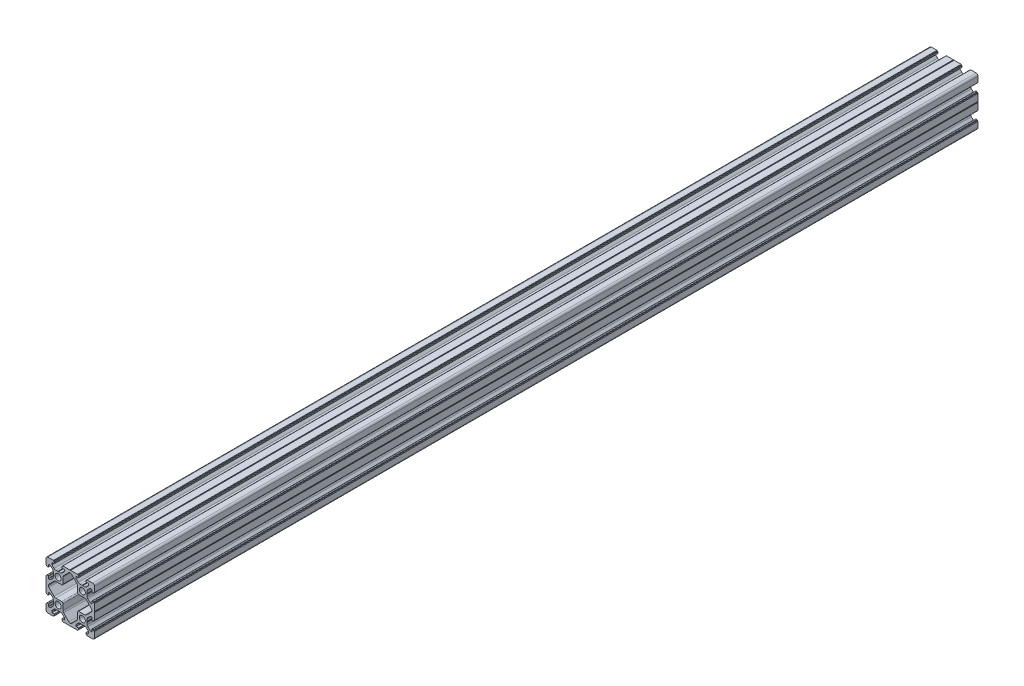
SolidWorks part; units mm, degrees
ref_plane "Спереди" through (0, 0, 0) normal (0, 0, 1) x (1, 0, 0)
ref_plane "Сверху" through (0, 0, 0) normal (0, 1, 0) x (1, 0, 0)
ref_plane "Справа" through (0, 0, 0) normal (1, 0, 0) x (0, 0, -1)
sketch "Эскиз3" plane through (0, 0, 0) normal (0, 0, 1) x (1, 0, 0)
  line L0 (-18.5, -18.5) -> (18.5, 18.5) construction
  line L1 (28.0099, -28.0099) -> (-35327.3285, 35327.3285) construction
  line L2 (-7, 6) -> (-11.9302, 6)
  line L3 (-13.3492, 5.4094) -> (-17.5933, 1.1367)
  line L4 (-18, 0.1501) -> (-18, -0.1501)
  line L5 (-13.3492, -5.4094) -> (-17.5933, -1.1367)
  line L6 (-7, -6) -> (-11.9302, -6)
  line L7 (6, -7) -> (6, -11.9302)
  line L8 (-6, -7) -> (-6, -11.9302)
  line L9 (-5.4094, -13.3492) -> (-1.1367, -17.5933)
  line L10 (-0.1501, -18) -> (0.1501, -18)
  line L11 (5.4094, -13.3492) -> (1.1367, -17.5933)
  line L12 (6, 7) -> (6, 11.9302)
  line L13 (5.4094, 13.3492) -> (1.1367, 17.5933)
  line L14 (0.1501, 18) -> (-0.1501, 18)
  line L15 (-5.4094, 13.3492) -> (-1.1367, 17.5933)
  line L16 (-6, 7) -> (-6, 11.9302)
  line L17 (7, -6) -> (11.9302, -6)
  line L18 (13.3492, -5.4094) -> (17.5933, -1.1367)
  line L19 (18, -0.1501) -> (18, 0.1501)
  line L20 (13.3492, 5.4094) -> (17.5933, 1.1367)
  line L21 (7, 6) -> (11.9302, 6)
  line L544 (0.237, 19.958) -> (0, 19.8)
  line L545 (0, 19.8) -> (-0.237, 19.958)
  line L546 (-0.3757, 20) -> (-6.05, 20)
  line L547 (-6.3, 19.75) -> (-6.3, 19.4)
  line L548 (-6.3, 19.4) -> (-6.68, 19.4)
  line L549 (-6.93, 19.15) -> (-6.93, 18.25)
  line L550 (-6.68, 18) -> (-5, 18)
  line L551 (-4.8, 17.8) -> (-4.8, 16.8517)
  line L552 (-5.0929, 16.1445) -> (-6.6517, 14.5858)
  line L553 (-8.0659, 14) -> (-9.6623, 14)
  line L554 (-9.8185, 13.9452) -> (-10, 13.8)
  line L555 (-10, 13.8) -> (-10.1815, 13.9452)
  line L556 (-10.3377, 14) -> (-11.9341, 14)
  line L557 (-13.3483, 14.5858) -> (-14.9071, 16.1445)
  line L558 (-15.2, 16.8517) -> (-15.2, 17.8)
  line L559 (-15, 18) -> (-13.32, 18)
  line L560 (-13.07, 18.25) -> (-13.07, 19.15)
  line L561 (-13.32, 19.4) -> (-13.7, 19.4)
  line L562 (-13.7, 19.4) -> (-13.7, 19.75)
  line L563 (-13.95, 20) -> (-18.5, 20)
  line L564 (-20, 18.5) -> (-20, 13.95)
  line L565 (-19.75, 13.7) -> (-19.4, 13.7)
  line L566 (-19.4, 13.7) -> (-19.4, 13.32)
  line L567 (-19.15, 13.07) -> (-18.25, 13.07)
  line L568 (-18, 13.32) -> (-18, 15)
  line L569 (-17.8, 15.2) -> (-16.8517, 15.2)
  line L570 (-16.1445, 14.9071) -> (-14.5858, 13.3483)
  line L571 (-14, 11.9341) -> (-14, 10.3377)
  line L572 (-13.9452, 10.1815) -> (-13.8, 10)
  line L573 (-13.8, 10) -> (-13.9452, 9.8185)
  line L574 (-14, 9.6623) -> (-14, 8.0659)
  line L575 (-14.5858, 6.6517) -> (-16.1445, 5.0929)
  line L576 (-16.8517, 4.8) -> (-17.8, 4.8)
  line L577 (-18, 5) -> (-18, 6.68)
  line L578 (-18.25, 6.93) -> (-19.15, 6.93)
  line L579 (-19.4, 6.68) -> (-19.4, 6.3)
  line L580 (-19.4, 6.3) -> (-19.75, 6.3)
  line L581 (-20, 6.05) -> (-20, 0.3757)
  line L582 (-19.958, 0.237) -> (-19.8, 0)
  line L583 (-19.8, 0) -> (-19.958, -0.237)
  line L584 (-20, -0.3757) -> (-20, -6.05)
  line L585 (-19.75, -6.3) -> (-19.4, -6.3)
  line L586 (-19.4, -6.3) -> (-19.4, -6.68)
  line L587 (-19.15, -6.93) -> (-18.25, -6.93)
  line L588 (-18, -6.68) -> (-18, -5)
  line L589 (-17.8, -4.8) -> (-16.8517, -4.8)
  line L590 (-16.1445, -5.0929) -> (-14.5858, -6.6517)
  line L591 (-14, -8.0659) -> (-14, -9.6623)
  line L592 (-13.9452, -9.8185) -> (-13.8, -10)
  line L593 (-13.8, -10) -> (-13.9452, -10.1815)
  line L594 (-14, -10.3377) -> (-14, -11.9341)
  line L595 (-14.5858, -13.3483) -> (-16.1445, -14.9071)
  line L596 (-16.8517, -15.2) -> (-17.8, -15.2)
  line L597 (-18, -15) -> (-18, -13.32)
  line L598 (-18.25, -13.07) -> (-19.15, -13.07)
  line L599 (-19.4, -13.32) -> (-19.4, -13.7)
  line L600 (-19.4, -13.7) -> (-19.75, -13.7)
  line L601 (-20, -13.95) -> (-20, -18.5)
  line L602 (-18.5, -20) -> (-13.95, -20)
  line L603 (-13.7, -19.75) -> (-13.7, -19.4)
  line L604 (-13.7, -19.4) -> (-13.32, -19.4)
  line L605 (-13.07, -19.15) -> (-13.07, -18.25)
  line L606 (-13.32, -18) -> (-15, -18)
  line L607 (-15.2, -17.8) -> (-15.2, -16.8517)
  line L608 (-14.9071, -16.1445) -> (-13.3483, -14.5858)
  line L609 (-11.9341, -14) -> (-10.3377, -14)
  line L610 (-10.1815, -13.9452) -> (-10, -13.8)
  line L611 (-10, -13.8) -> (-9.8185, -13.9452)
  line L612 (-9.6623, -14) -> (-8.0659, -14)
  line L613 (-6.6517, -14.5858) -> (-5.0929, -16.1445)
  line L614 (-4.8, -16.8517) -> (-4.8, -17.8)
  line L615 (-5, -18) -> (-6.68, -18)
  line L616 (-6.93, -18.25) -> (-6.93, -19.15)
  line L617 (-6.68, -19.4) -> (-6.3, -19.4)
  line L618 (-6.3, -19.4) -> (-6.3, -19.75)
  line L619 (-6.05, -20) -> (-0.3757, -20)
  line L620 (-0.237, -19.958) -> (0, -19.8)
  line L621 (0, -19.8) -> (0.237, -19.958)
  line L622 (0.3757, -20) -> (6.05, -20)
  line L623 (6.3, -19.75) -> (6.3, -19.4)
  line L624 (6.3, -19.4) -> (6.68, -19.4)
  line L625 (6.93, -19.15) -> (6.93, -18.25)
  line L626 (6.68, -18) -> (5, -18)
  line L627 (4.8, -17.8) -> (4.8, -16.8517)
  line L628 (5.0929, -16.1445) -> (6.6517, -14.5858)
  line L629 (8.0659, -14) -> (9.6623, -14)
  line L630 (9.8185, -13.9452) -> (10, -13.8)
  line L631 (10, -13.8) -> (10.1815, -13.9452)
  line L632 (10.3377, -14) -> (11.9341, -14)
  line L633 (13.3483, -14.5858) -> (14.9071, -16.1445)
  line L634 (15.2, -16.8517) -> (15.2, -17.8)
  line L635 (15, -18) -> (13.32, -18)
  line L636 (13.07, -18.25) -> (13.07, -19.15)
  line L637 (13.32, -19.4) -> (13.7, -19.4)
  line L638 (13.7, -19.4) -> (13.7, -19.75)
  line L639 (13.95, -20) -> (18.5, -20)
  line L640 (20, -18.5) -> (20, -13.95)
  line L641 (19.75, -13.7) -> (19.4, -13.7)
  line L642 (19.4, -13.7) -> (19.4, -13.32)
  line L643 (19.15, -13.07) -> (18.25, -13.07)
  line L644 (18, -13.32) -> (18, -15)
  line L645 (17.8, -15.2) -> (16.8517, -15.2)
  line L646 (16.1445, -14.9071) -> (14.5858, -13.3483)
  line L647 (14, -11.9341) -> (14, -10.3377)
  line L648 (13.9452, -10.1815) -> (13.8, -10)
  line L649 (13.8, -10) -> (13.9452, -9.8185)
  line L650 (14, -9.6623) -> (14, -8.0659)
  line L651 (14.5858, -6.6517) -> (16.1445, -5.0929)
  line L652 (16.8517, -4.8) -> (17.8, -4.8)
  line L653 (18, -5) -> (18, -6.68)
  line L654 (18.25, -6.93) -> (19.15, -6.93)
  line L655 (19.4, -6.68) -> (19.4, -6.3)
  line L656 (19.4, -6.3) -> (19.75, -6.3)
  line L657 (20, -6.05) -> (20, -0.3757)
  line L658 (19.958, -0.237) -> (19.8, 0)
  line L659 (19.8, 0) -> (19.958, 0.237)
  line L660 (20, 0.3757) -> (20, 6.05)
  line L661 (19.75, 6.3) -> (19.4, 6.3)
  line L662 (19.4, 6.3) -> (19.4, 6.68)
  line L663 (19.15, 6.93) -> (18.25, 6.93)
  line L664 (18, 6.68) -> (18, 5)
  line L665 (17.8, 4.8) -> (16.8517, 4.8)
  line L666 (16.1445, 5.0929) -> (14.5858, 6.6517)
  line L667 (14, 8.0659) -> (14, 9.6623)
  line L668 (13.9452, 9.8185) -> (13.8, 10)
  line L669 (13.8, 10) -> (13.9452, 10.1815)
  line L670 (14, 10.3377) -> (14, 11.9341)
  line L671 (14.5858, 13.3483) -> (16.1445, 14.9071)
  line L672 (16.8517, 15.2) -> (17.8, 15.2)
  line L673 (18, 15) -> (18, 13.32)
  line L674 (18.25, 13.07) -> (19.15, 13.07)
  line L675 (19.4, 13.32) -> (19.4, 13.7)
  line L676 (19.4, 13.7) -> (19.75, 13.7)
  line L677 (20, 13.95) -> (20, 18.5)
  line L678 (18.5, 20) -> (13.95, 20)
  line L679 (13.7, 19.75) -> (13.7, 19.4)
  line L680 (13.7, 19.4) -> (13.32, 19.4)
  line L681 (13.07, 19.15) -> (13.07, 18.25)
  line L682 (13.32, 18) -> (15, 18)
  line L683 (15.2, 17.8) -> (15.2, 16.8517)
  line L684 (14.9071, 16.1445) -> (13.3483, 14.5858)
  line L685 (11.9341, 14) -> (10.3377, 14)
  line L686 (10.1815, 13.9452) -> (10, 13.8)
  line L687 (10, 13.8) -> (9.8185, 13.9452)
  line L688 (9.6623, 14) -> (8.0659, 14)
  line L689 (6.6517, 14.5858) -> (5.0929, 16.1445)
  line L690 (4.8, 16.8517) -> (4.8, 17.8)
  line L691 (5, 18) -> (6.68, 18)
  line L692 (6.93, 18.25) -> (6.93, 19.15)
  line L693 (6.68, 19.4) -> (6.3, 19.4)
  line L694 (6.3, 19.4) -> (6.3, 19.75)
  line L695 (6.05, 20) -> (0.3757, 20)
  arc A0 (-7, 6) -> (-6, 7) centre (-7, 7) ccw
  arc A1 (-11.9302, 6) -> (-13.3492, 5.4094) centre (-11.9302, 4) ccw
  arc A2 (-17.5933, 1.1367) -> (-18, 0.1501) centre (-16.6, 0.1501) ccw
  arc A3 (-18, -0.1501) -> (-17.5933, -1.1367) centre (-16.6, -0.1501) ccw
  arc A4 (-13.3492, -5.4094) -> (-11.9302, -6) centre (-11.9302, -4) ccw
  arc A5 (6, 7) -> (7, 6) centre (7, 7) ccw
  arc A6 (6, 11.9302) -> (5.4094, 13.3492) centre (4, 11.9302) ccw
  arc A7 (1.1367, 17.5933) -> (0.1501, 18) centre (0.1501, 16.6) ccw
  arc A8 (7.5, 10) -> (12.5, 10) centre (10, 10) ccw
  arc A9 (12.5, 10) -> (7.5, 10) centre (10, 10) ccw
  arc A10 (-7.5, 10) -> (-12.5, 10) centre (-10, 10) ccw
  arc A11 (-12.5, 10) -> (-7.5, 10) centre (-10, 10) ccw
  arc A12 (-7.5, -10) -> (-12.5, -10) centre (-10, -10) ccw
  arc A13 (-12.5, -10) -> (-7.5, -10) centre (-10, -10) ccw
  arc A14 (12.5, -10) -> (7.5, -10) centre (10, -10) ccw
  arc A15 (7.5, -10) -> (12.5, -10) centre (10, -10) ccw
  arc A16 (-0.1501, 18) -> (-1.1367, 17.5933) centre (-0.1501, 16.6) ccw
  arc A17 (-5.4094, 13.3492) -> (-6, 11.9302) centre (-4, 11.9302) ccw
  arc A18 (7, -6) -> (6, -7) centre (7, -7) ccw
  arc A19 (11.9302, -6) -> (13.3492, -5.4094) centre (11.9302, -4) ccw
  arc A20 (17.5933, -1.1367) -> (18, -0.1501) centre (16.6, -0.1501) ccw
  arc A21 (18, 0.1501) -> (17.5933, 1.1367) centre (16.6, 0.1501) ccw
  arc A22 (13.3492, 5.4094) -> (11.9302, 6) centre (11.9302, 4) ccw
  arc A23 (5.4094, -13.3492) -> (6, -11.9302) centre (4, -11.9302) ccw
  arc A24 (-6, -7) -> (-7, -6) centre (-7, -7) ccw
  arc A25 (-6, -11.9302) -> (-5.4094, -13.3492) centre (-4, -11.9302) ccw
  arc A26 (-1.1367, -17.5933) -> (-0.1501, -18) centre (-0.1501, -16.6) ccw
  arc A27 (0.1501, -18) -> (1.1367, -17.5933) centre (0.1501, -16.6) ccw
  arc A464 (-0.237, 19.958) -> (-0.3757, 20) centre (-0.3757, 19.75) ccw
  arc A465 (-6.05, 20) -> (-6.3, 19.75) centre (-6.05, 19.75) ccw
  arc A466 (-6.68, 19.4) -> (-6.93, 19.15) centre (-6.68, 19.15) ccw
  arc A467 (-6.93, 18.25) -> (-6.68, 18) centre (-6.68, 18.25) ccw
  arc A468 (-4.8, 17.8) -> (-5, 18) centre (-5, 17.8) ccw
  arc A469 (-5.0929, 16.1445) -> (-4.8, 16.8517) centre (-5.8, 16.8517) ccw
  arc A470 (-8.0659, 14) -> (-6.6517, 14.5858) centre (-8.0659, 16) ccw
  arc A471 (-9.6623, 14) -> (-9.8185, 13.9452) centre (-9.6623, 13.75) ccw
  arc A472 (-10.1815, 13.9452) -> (-10.3377, 14) centre (-10.3377, 13.75) ccw
  arc A473 (-13.3483, 14.5858) -> (-11.9341, 14) centre (-11.9341, 16) ccw
  arc A474 (-15.2, 16.8517) -> (-14.9071, 16.1445) centre (-14.2, 16.8517) ccw
  arc A475 (-15, 18) -> (-15.2, 17.8) centre (-15, 17.8) ccw
  arc A476 (-13.32, 18) -> (-13.07, 18.25) centre (-13.32, 18.25) ccw
  arc A477 (-13.07, 19.15) -> (-13.32, 19.4) centre (-13.32, 19.15) ccw
  arc A478 (-13.7, 19.75) -> (-13.95, 20) centre (-13.95, 19.75) ccw
  arc A479 (-18.5, 20) -> (-20, 18.5) centre (-18.5, 18.5) ccw
  arc A480 (-20, 13.95) -> (-19.75, 13.7) centre (-19.75, 13.95) ccw
  arc A481 (-19.4, 13.32) -> (-19.15, 13.07) centre (-19.15, 13.32) ccw
  arc A482 (-18.25, 13.07) -> (-18, 13.32) centre (-18.25, 13.32) ccw
  arc A483 (-17.8, 15.2) -> (-18, 15) centre (-17.8, 15) ccw
  arc A484 (-16.1445, 14.9071) -> (-16.8517, 15.2) centre (-16.8517, 14.2) ccw
  arc A485 (-14, 11.9341) -> (-14.5858, 13.3483) centre (-16, 11.9341) ccw
  arc A486 (-14, 10.3377) -> (-13.9452, 10.1815) centre (-13.75, 10.3377) ccw
  arc A487 (-13.9452, 9.8185) -> (-14, 9.6623) centre (-13.75, 9.6623) ccw
  arc A488 (-14.5858, 6.6517) -> (-14, 8.0659) centre (-16, 8.0659) ccw
  arc A489 (-16.8517, 4.8) -> (-16.1445, 5.0929) centre (-16.8517, 5.8) ccw
  arc A490 (-18, 5) -> (-17.8, 4.8) centre (-17.8, 5) ccw
  arc A491 (-18, 6.68) -> (-18.25, 6.93) centre (-18.25, 6.68) ccw
  arc A492 (-19.15, 6.93) -> (-19.4, 6.68) centre (-19.15, 6.68) ccw
  arc A493 (-19.75, 6.3) -> (-20, 6.05) centre (-19.75, 6.05) ccw
  arc A494 (-20, 0.3757) -> (-19.958, 0.237) centre (-19.75, 0.3757) ccw
  arc A495 (-19.958, -0.237) -> (-20, -0.3757) centre (-19.75, -0.3757) ccw
  arc A496 (-20, -6.05) -> (-19.75, -6.3) centre (-19.75, -6.05) ccw
  arc A497 (-19.4, -6.68) -> (-19.15, -6.93) centre (-19.15, -6.68) ccw
  arc A498 (-18.25, -6.93) -> (-18, -6.68) centre (-18.25, -6.68) ccw
  arc A499 (-17.8, -4.8) -> (-18, -5) centre (-17.8, -5) ccw
  arc A500 (-16.1445, -5.0929) -> (-16.8517, -4.8) centre (-16.8517, -5.8) ccw
  arc A501 (-14, -8.0659) -> (-14.5858, -6.6517) centre (-16, -8.0659) ccw
  arc A502 (-14, -9.6623) -> (-13.9452, -9.8185) centre (-13.75, -9.6623) ccw
  arc A503 (-13.9452, -10.1815) -> (-14, -10.3377) centre (-13.75, -10.3377) ccw
  arc A504 (-14.5858, -13.3483) -> (-14, -11.9341) centre (-16, -11.9341) ccw
  arc A505 (-16.8517, -15.2) -> (-16.1445, -14.9071) centre (-16.8517, -14.2) ccw
  arc A506 (-18, -15) -> (-17.8, -15.2) centre (-17.8, -15) ccw
  arc A507 (-18, -13.32) -> (-18.25, -13.07) centre (-18.25, -13.32) ccw
  arc A508 (-19.15, -13.07) -> (-19.4, -13.32) centre (-19.15, -13.32) ccw
  arc A509 (-19.75, -13.7) -> (-20, -13.95) centre (-19.75, -13.95) ccw
  arc A510 (-20, -18.5) -> (-18.5, -20) centre (-18.5, -18.5) ccw
  arc A511 (-13.95, -20) -> (-13.7, -19.75) centre (-13.95, -19.75) ccw
  arc A512 (-13.32, -19.4) -> (-13.07, -19.15) centre (-13.32, -19.15) ccw
  arc A513 (-13.07, -18.25) -> (-13.32, -18) centre (-13.32, -18.25) ccw
  arc A514 (-15.2, -17.8) -> (-15, -18) centre (-15, -17.8) ccw
  arc A515 (-14.9071, -16.1445) -> (-15.2, -16.8517) centre (-14.2, -16.8517) ccw
  arc A516 (-11.9341, -14) -> (-13.3483, -14.5858) centre (-11.9341, -16) ccw
  arc A517 (-10.3377, -14) -> (-10.1815, -13.9452) centre (-10.3377, -13.75) ccw
  arc A518 (-9.8185, -13.9452) -> (-9.6623, -14) centre (-9.6623, -13.75) ccw
  arc A519 (-6.6517, -14.5858) -> (-8.0659, -14) centre (-8.0659, -16) ccw
  arc A520 (-4.8, -16.8517) -> (-5.0929, -16.1445) centre (-5.8, -16.8517) ccw
  arc A521 (-5, -18) -> (-4.8, -17.8) centre (-5, -17.8) ccw
  arc A522 (-6.68, -18) -> (-6.93, -18.25) centre (-6.68, -18.25) ccw
  arc A523 (-6.93, -19.15) -> (-6.68, -19.4) centre (-6.68, -19.15) ccw
  arc A524 (-6.3, -19.75) -> (-6.05, -20) centre (-6.05, -19.75) ccw
  arc A525 (-0.3757, -20) -> (-0.237, -19.958) centre (-0.3757, -19.75) ccw
  arc A526 (0.237, -19.958) -> (0.3757, -20) centre (0.3757, -19.75) ccw
  arc A527 (6.05, -20) -> (6.3, -19.75) centre (6.05, -19.75) ccw
  arc A528 (6.68, -19.4) -> (6.93, -19.15) centre (6.68, -19.15) ccw
  arc A529 (6.93, -18.25) -> (6.68, -18) centre (6.68, -18.25) ccw
  arc A530 (4.8, -17.8) -> (5, -18) centre (5, -17.8) ccw
  arc A531 (5.0929, -16.1445) -> (4.8, -16.8517) centre (5.8, -16.8517) ccw
  arc A532 (8.0659, -14) -> (6.6517, -14.5858) centre (8.0659, -16) ccw
  arc A533 (9.6623, -14) -> (9.8185, -13.9452) centre (9.6623, -13.75) ccw
  arc A534 (10.1815, -13.9452) -> (10.3377, -14) centre (10.3377, -13.75) ccw
  arc A535 (13.3483, -14.5858) -> (11.9341, -14) centre (11.9341, -16) ccw
  arc A536 (15.2, -16.8517) -> (14.9071, -16.1445) centre (14.2, -16.8517) ccw
  arc A537 (15, -18) -> (15.2, -17.8) centre (15, -17.8) ccw
  arc A538 (13.32, -18) -> (13.07, -18.25) centre (13.32, -18.25) ccw
  arc A539 (13.07, -19.15) -> (13.32, -19.4) centre (13.32, -19.15) ccw
  arc A540 (13.7, -19.75) -> (13.95, -20) centre (13.95, -19.75) ccw
  arc A541 (18.5, -20) -> (20, -18.5) centre (18.5, -18.5) ccw
  arc A542 (20, -13.95) -> (19.75, -13.7) centre (19.75, -13.95) ccw
  arc A543 (19.4, -13.32) -> (19.15, -13.07) centre (19.15, -13.32) ccw
  arc A544 (18.25, -13.07) -> (18, -13.32) centre (18.25, -13.32) ccw
  arc A545 (17.8, -15.2) -> (18, -15) centre (17.8, -15) ccw
  arc A546 (16.1445, -14.9071) -> (16.8517, -15.2) centre (16.8517, -14.2) ccw
  arc A547 (14, -11.9341) -> (14.5858, -13.3483) centre (16, -11.9341) ccw
  arc A548 (14, -10.3377) -> (13.9452, -10.1815) centre (13.75, -10.3377) ccw
  arc A549 (13.9452, -9.8185) -> (14, -9.6623) centre (13.75, -9.6623) ccw
  arc A550 (14.5858, -6.6517) -> (14, -8.0659) centre (16, -8.0659) ccw
  arc A551 (16.8517, -4.8) -> (16.1445, -5.0929) centre (16.8517, -5.8) ccw
  arc A552 (18, -5) -> (17.8, -4.8) centre (17.8, -5) ccw
  arc A553 (18, -6.68) -> (18.25, -6.93) centre (18.25, -6.68) ccw
  arc A554 (19.15, -6.93) -> (19.4, -6.68) centre (19.15, -6.68) ccw
  arc A555 (19.75, -6.3) -> (20, -6.05) centre (19.75, -6.05) ccw
  arc A556 (20, -0.3757) -> (19.958, -0.237) centre (19.75, -0.3757) ccw
  arc A557 (19.958, 0.237) -> (20, 0.3757) centre (19.75, 0.3757) ccw
  arc A558 (20, 6.05) -> (19.75, 6.3) centre (19.75, 6.05) ccw
  arc A559 (19.4, 6.68) -> (19.15, 6.93) centre (19.15, 6.68) ccw
  arc A560 (18.25, 6.93) -> (18, 6.68) centre (18.25, 6.68) ccw
  arc A561 (17.8, 4.8) -> (18, 5) centre (17.8, 5) ccw
  arc A562 (16.1445, 5.0929) -> (16.8517, 4.8) centre (16.8517, 5.8) ccw
  arc A563 (14, 8.0659) -> (14.5858, 6.6517) centre (16, 8.0659) ccw
  arc A564 (14, 9.6623) -> (13.9452, 9.8185) centre (13.75, 9.6623) ccw
  arc A565 (13.9452, 10.1815) -> (14, 10.3377) centre (13.75, 10.3377) ccw
  arc A566 (14.5858, 13.3483) -> (14, 11.9341) centre (16, 11.9341) ccw
  arc A567 (16.8517, 15.2) -> (16.1445, 14.9071) centre (16.8517, 14.2) ccw
  arc A568 (18, 15) -> (17.8, 15.2) centre (17.8, 15) ccw
  arc A569 (18, 13.32) -> (18.25, 13.07) centre (18.25, 13.32) ccw
  arc A570 (19.15, 13.07) -> (19.4, 13.32) centre (19.15, 13.32) ccw
  arc A571 (19.75, 13.7) -> (20, 13.95) centre (19.75, 13.95) ccw
  arc A572 (20, 18.5) -> (18.5, 20) centre (18.5, 18.5) ccw
  arc A573 (13.95, 20) -> (13.7, 19.75) centre (13.95, 19.75) ccw
  arc A574 (13.32, 19.4) -> (13.07, 19.15) centre (13.32, 19.15) ccw
  arc A575 (13.07, 18.25) -> (13.32, 18) centre (13.32, 18.25) ccw
  arc A576 (15.2, 17.8) -> (15, 18) centre (15, 17.8) ccw
  arc A577 (14.9071, 16.1445) -> (15.2, 16.8517) centre (14.2, 16.8517) ccw
  arc A578 (11.9341, 14) -> (13.3483, 14.5858) centre (11.9341, 16) ccw
  arc A579 (10.3377, 14) -> (10.1815, 13.9452) centre (10.3377, 13.75) ccw
  arc A580 (9.8185, 13.9452) -> (9.6623, 14) centre (9.6623, 13.75) ccw
  arc A581 (6.6517, 14.5858) -> (8.0659, 14) centre (8.0659, 16) ccw
  arc A582 (4.8, 16.8517) -> (5.0929, 16.1445) centre (5.8, 16.8517) ccw
  arc A583 (5, 18) -> (4.8, 17.8) centre (5, 17.8) ccw
  arc A584 (6.68, 18) -> (6.93, 18.25) centre (6.68, 18.25) ccw
  arc A585 (6.93, 19.15) -> (6.68, 19.4) centre (6.68, 19.15) ccw
  arc A586 (6.3, 19.75) -> (6.05, 20) centre (6.05, 19.75) ccw
  arc A587 (0.3757, 20) -> (0.237, 19.958) centre (0.3757, 19.75) ccw
  point P355 (0, 0)
  dimension "D1" = 4
extrude "Бобышка-Вытянуть2" add sketch "Эскиз3" along normal blind 730
